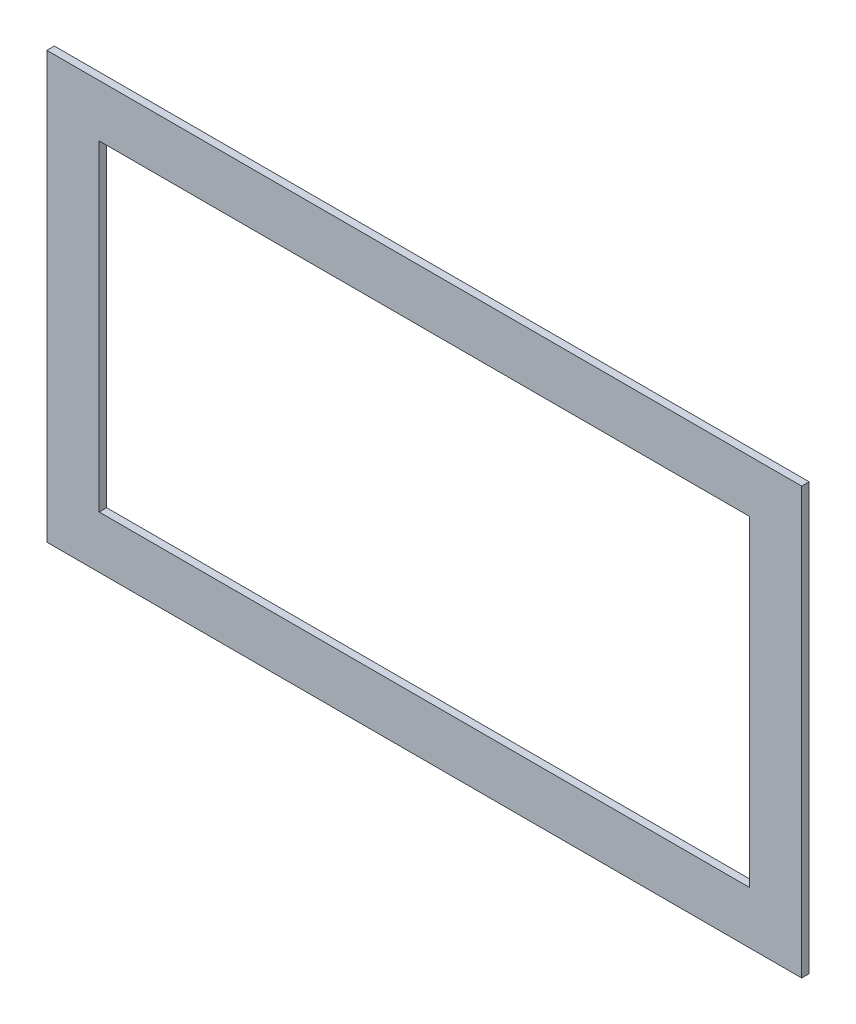
SolidWorks part; units mm, degrees
ref_plane "Front Plane" through (0, 0, 0) normal (0, 0, 1) x (1, 0, 0)
ref_plane "Top Plane" through (0, 0, 0) normal (0, 1, 0) x (1, 0, 0)
ref_plane "Right Plane" through (0, 0, 0) normal (1, 0, 0) x (0, 0, -1)
sketch "Sketch1" plane through (0, 0, 0) normal (0, 0, 1) x (1, 0, 0)
  line L1 (0, 0) -> (101, 0)
  line L2 (0, 0) -> (0, 57)
  line L3 (0, 57) -> (101, 57)
  line L4 (101, 0) -> (101, 57)
  line L5 (7, 7) -> (94, 7)
  line L6 (7, 7) -> (7, 50)
  line L7 (7, 50) -> (94, 50)
  line L8 (94, 7) -> (94, 50)
  dimension "D1" = 7
  dimension "D2" = 94
  dimension "D3" = 101
  dimension "D4" = 7
  dimension "D5" = 50
  dimension "D6" = 57
extrude "Profile" add sketch "Sketch1" along normal blind 1
equation "\"Profile_Depth\" = 1mm"
equation "\"D1@Profile\" = \"Profile_Depth\""
equation "\"EnvelopeWidth\" = 101mm"
equation "\"EnvelopeHeight\" = 57mm"
